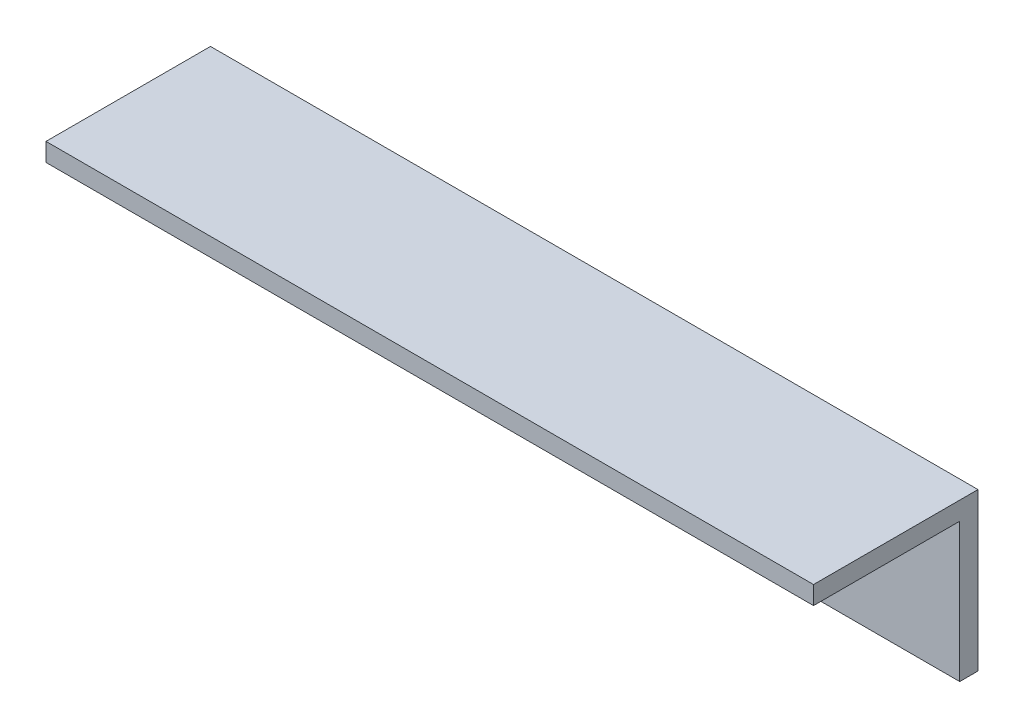
SolidWorks part; units mm, degrees
material "AISI 4130 Steel, annealed at 865C"
ref_plane "Front Plane" through (0, 0, 0) normal (0, 0, 1) x (1, 0, 0)
ref_plane "Top Plane" through (0, 0, 0) normal (0, 1, 0) x (1, 0, 0)
ref_plane "Right Plane" through (0, 0, 0) normal (1, 0, 0) x (0, 0, -1)
sketch "Sketch1" plane through (0, 0, 0) normal (0, 0, 1) x (1, 0, 0)
  line L0 (-66.675, 162.56) -> (-66.675, 138.43) construction
  line L1 (66.675, 162.56) -> (66.675, 138.43) construction
  line L2 (-66.675, 162.56) -> (-66.675, 138.43)
  line L3 (66.675, 162.56) -> (66.675, 138.43)
  line L5 (-66.675, 138.43) -> (66.675, 138.43)
  line L6 (-66.675, 162.56) -> (-66.675, 165.735)
  line L7 (-66.675, 165.735) -> (66.675, 165.735)
  line L8 (66.675, 165.735) -> (66.675, 162.56)
  circle A0 centre (51.435, 153.67) radius 3.5712 construction
  circle A1 centre (-51.435, 153.67) radius 3.5712 construction
  circle A2 centre (51.435, 153.67) radius 3.5712
  circle A3 centre (-51.435, 153.67) radius 3.5712
  dimension "D1" = 3.175
extrude "Boss-Extrude1" add sketch "Sketch1" along normal blind 3.175
sketch "Sketch2" plane through (0, 0, 3.175) normal (0, 0, 1) x (1, 0, 0)
  line L0 (66.675, 165.735) -> (-66.675, 165.735) construction
  line L1 (66.675, 165.735) -> (-66.675, 165.735)
  line L2 (66.675, 162.56) -> (-66.675, 162.56)
  line L3 (-66.675, 162.56) -> (-66.675, 165.735)
  line L4 (66.675, 165.735) -> (66.675, 162.56)
  dimension "D1" = 3.175
extrude "Boss-Extrude2" add sketch "Sketch2" along normal blind 25.4
